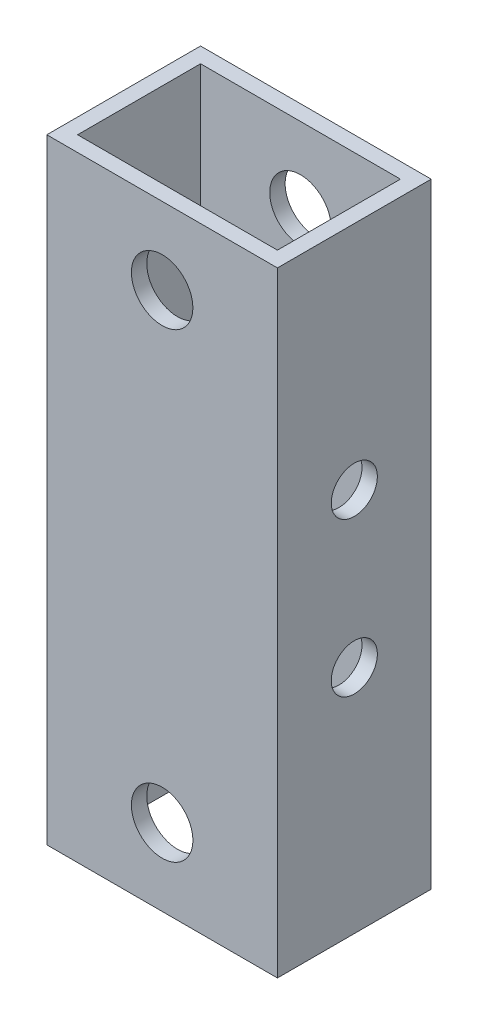
SolidWorks part; units mm, degrees
material "5052-H34"
ref_plane "正面" through (0, 0, 0) normal (0, 0, 1) x (1, 0, 0)
ref_plane "平面" through (0, 0, 0) normal (0, 1, 0) x (1, 0, 0)
ref_plane "右側面" through (0, 0, 0) normal (1, 0, 0) x (0, 0, -1)
sketch "ｽｹｯﾁ1" plane through (0, 0, 0) normal (0, 1, 0) x (1, 0, 0)
  line L1 (0, 0) -> (15, 0)
  line L2 (0, 0) -> (0, 10)
  line L3 (0, 10) -> (15, 10)
  line L4 (15, 0) -> (15, 10)
  dimension "D1" = 15
  dimension "D2" = 10
extrude "押し出し-薄板1" add sketch "ｽｹｯﾁ1" along normal blind 40 thin thin type one direction reverse wall 1
sketch "ｽｹｯﾁ3" plane through (15, 0, 0) normal (1, 0, 0) x (0, 0, -1)
  line L0 (5, 40) -> (5, 0) construction
  line L1 (0, 40) -> (10, 40) construction
  line L2 (0, 0) -> (10, 0) construction
  circle A0 centre (5, 25) radius 1.5
  circle A1 centre (5, 15) radius 1.5
  dimension "D1" = 15
  dimension "D2" = 10
  dimension "D3" = 3
extrude "ｶｯﾄ - 押し出し1" cut sketch "ｽｹｯﾁ3" against normal up to surface (15 mm away) up to face at (0, 20, -5)
sketch "ｽｹｯﾁ4" plane through (0, 0, 0) normal (0, 0, 1) x (1, 0, 0)
  line L0 (7.5, 40) -> (7.5, 0) construction
  line L1 (0, 40) -> (15, 40) construction
  line L2 (0, 0) -> (15, 0) construction
  line L3 (15, 20) -> (0, 20) construction
  line L4 (15, 40) -> (15, 0) construction
  line L5 (0, 40) -> (0, 0) construction
  circle A0 centre (7.5, 35) radius 2
  circle A1 centre (7.5, 5) radius 2
  dimension "D1" = 4
  dimension "D2" = 5
  dimension "D3" = 30
extrude "ｶｯﾄ - 押し出し2" cut sketch "ｽｹｯﾁ4" against normal up to surface (10 mm away) up to face at (7.5, 20, -10)
